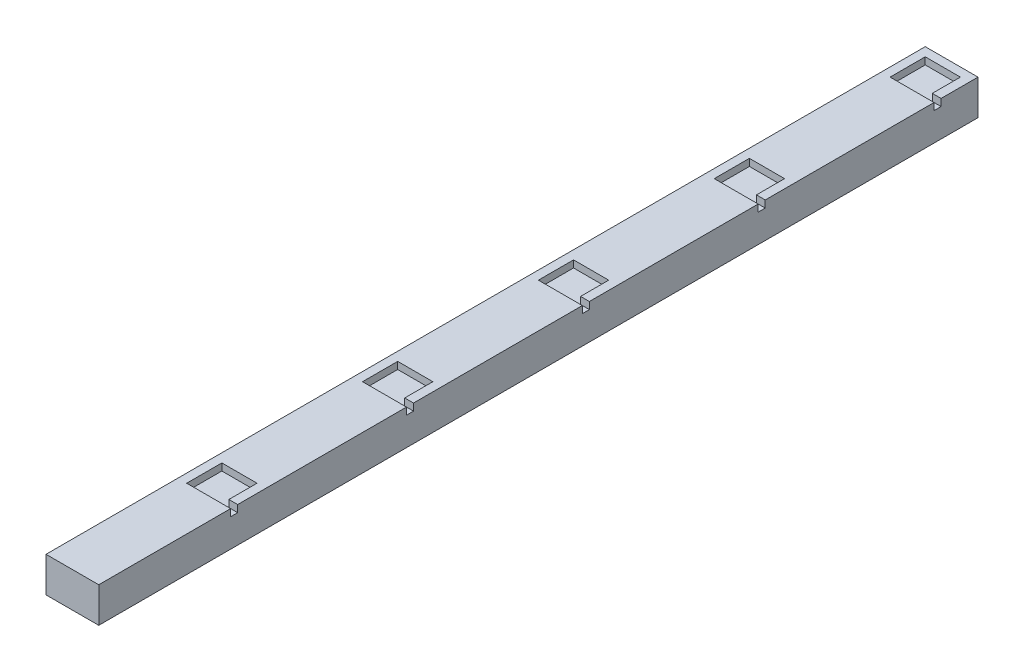
SolidWorks part; units mm, degrees
ref_plane "Front Plane" through (0, 0, 0) normal (0, 0, 1) x (1, 0, 0)
ref_plane "Top Plane" through (0, 0, 0) normal (0, 1, 0) x (1, 0, 0)
ref_plane "Right Plane" through (0, 0, 0) normal (1, 0, 0) x (0, 0, -1)
sketch "Sketch1" plane through (0, 0, 0) normal (0, 1, 0) x (1, 0, 0)
  line L1 (0, 300) -> (15, 300)
  line L2 (0, 300) -> (0, 0)
  line L3 (0, 0) -> (15, 0)
  line L4 (15, 300) -> (15, 0)
  point P4 (0, 0)
  point P6 (24.3892, 77.6232)
  point P7 (30.4865, 95.2116)
extrude "Boss-Extrude1" add sketch "Sketch1" along normal blind 10
sketch "Sketch2" plane through (0, 10, 0) normal (0, 1, 0) x (1, 0, 0)
  line L0 (15, 0) -> (15, 300) construction
  line L1 (2.5, 297.5) -> (12.5, 297.5)
  line L2 (2.5, 297.5) -> (2.5, 287.5)
  line L3 (2.5, 287.5) -> (12.5, 287.5)
  line L5 (12.5, 287.5) -> (15, 287.5)
  line L7 (12.5, 289.5) -> (15, 289.5)
  line L8 (15, 287.5) -> (15, 289.5)
  line L9 (12.5, 297.5) -> (12.5, 289.5)
extrude "Cut-Extrude2" cut sketch "Sketch2" against normal blind 2
sketch "Sketch3" plane through (0, 10, 0) normal (0, 1, 0) x (1, 0, 0)
  line L0 (15, 0) -> (15, 287.5) construction
  line L1 (2.5, 247.5) -> (12.5, 247.5)
  line L2 (2.5, 247.5) -> (2.5, 237.5)
  line L3 (2.5, 237.5) -> (12.5, 237.5)
  line L5 (12.5, 237.5) -> (15, 237.5)
  line L7 (12.5, 239.5) -> (15, 239.5)
  line L8 (15, 237.5) -> (15, 239.5)
  line L9 (12.5, 247.5) -> (12.5, 239.5)
extrude "Cut-Extrude3" cut sketch "Sketch3" against normal blind 2
sketch "Sketch4" plane through (0, 10, 0) normal (0, 1, 0) x (1, 0, 0)
  line L0 (12.5, 187.5) -> (15, 187.5)
  line L1 (2.5, 197.5) -> (12.5, 197.5)
  line L2 (2.5, 197.5) -> (2.5, 187.5)
  line L3 (2.5, 187.5) -> (12.5, 187.5)
  line L5 (15, 0) -> (15, 237.5) construction
  line L6 (12.5, 189.5) -> (15, 189.5)
  line L7 (12.5, 197.5) -> (12.5, 189.5)
  line L8 (15, 189.5) -> (15, 187.5)
extrude "Cut-Extrude4" cut sketch "Sketch4" against normal blind 2
sketch "Sketch5" plane through (0, 10, 0) normal (0, 1, 0) x (1, 0, 0)
  line L0 (12.5, 137.5) -> (15, 137.5)
  line L1 (2.5, 147.5) -> (12.5, 147.5)
  line L2 (2.5, 147.5) -> (2.5, 137.5)
  line L3 (2.5, 137.5) -> (12.5, 137.5)
  line L5 (15, 0) -> (15, 187.5) construction
  line L6 (12.5, 139.5) -> (15, 139.5)
  line L7 (12.5, 139.5) -> (12.5, 147.5)
  line L8 (15, 139.5) -> (15, 137.5)
extrude "Cut-Extrude5" cut sketch "Sketch5" against normal blind 2
sketch "Sketch6" plane through (0, 10, 0) normal (0, 1, 0) x (1, 0, 0)
  line L0 (12.5, 87.5) -> (15, 87.5)
  line L1 (2.5, 97.5) -> (12.5, 97.5)
  line L2 (2.5, 97.5) -> (2.5, 87.5)
  line L3 (2.5, 87.5) -> (12.5, 87.5)
  line L5 (15, 0) -> (15, 137.5) construction
  line L6 (12.5, 89.5) -> (15, 89.5)
  line L7 (15, 89.5) -> (15, 87.5)
  line L8 (12.5, 89.5) -> (12.5, 97.5)
extrude "Cut-Extrude6" cut sketch "Sketch6" against normal blind 2
sketch "Sketch8" plane through (0, 0, 0) normal (0, 0, 1) x (1, 0, 0)
  line L1 (0, 10) -> (15, 10)
  line L2 (0, 10) -> (0, 0)
  line L3 (0, 0) -> (15, 0)
  line L4 (15, 10) -> (15, 0)
extrude "Cut-Extrude7" cut sketch "Sketch8" against normal blind 50
